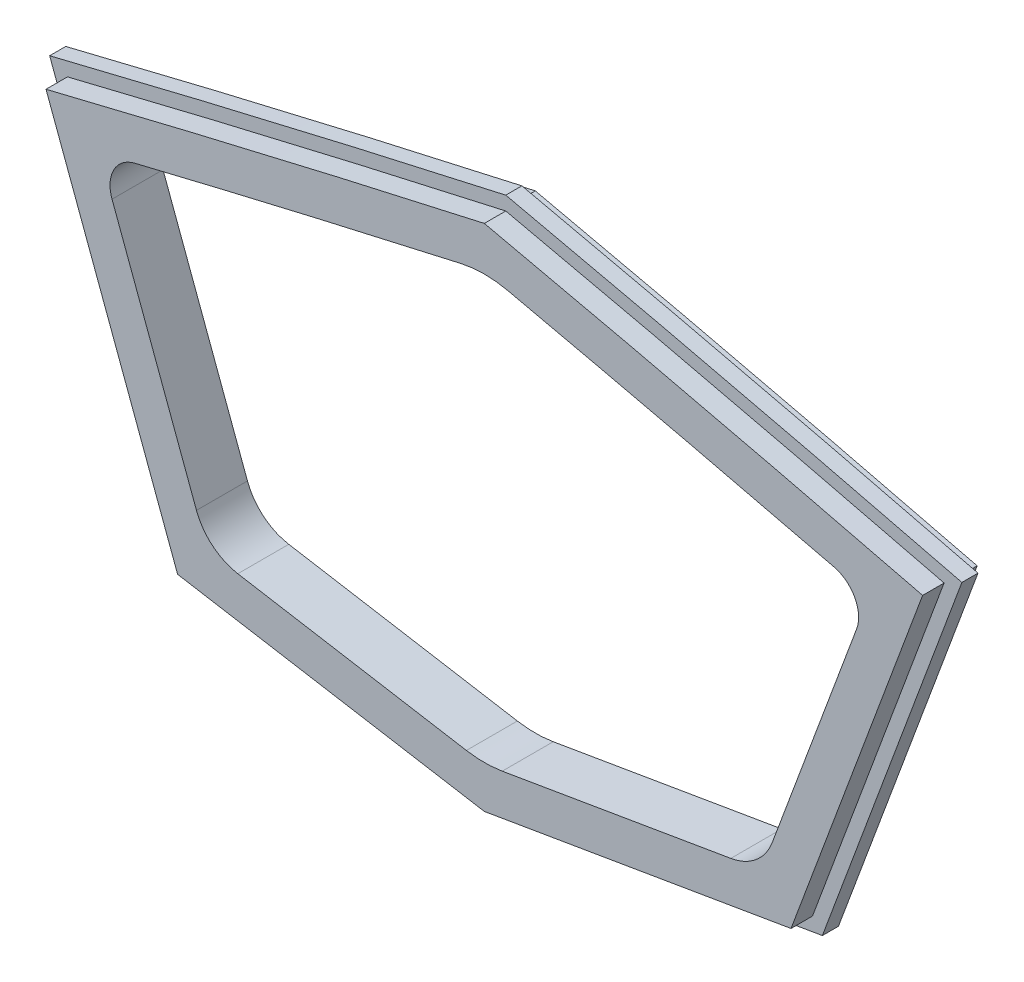
SolidWorks part; units mm, degrees
ref_plane "Front Plane" through (0, 0, 0) normal (0, 0, 1) x (1, 0, 0)
ref_plane "Top Plane" through (0, 0, 0) normal (0, 1, 0) x (1, 0, 0)
ref_plane "Right Plane" through (0, 0, 0) normal (1, 0, 0) x (0, 0, -1)
sketch "Sketch1" plane through (0, 0, 0) normal (0, 0, 1) x (1, 0, 0)
  line L0 (51.6321, -61.1055) -> (71.7233, -7.0229)
  line L1 (-71.7233, -7.0229) -> (-51.6321, -61.1055)
  line L2 (-51.6321, -61.1055) -> (0, -69.8574)
  line L3 (0, -69.8574) -> (51.6321, -61.1055)
  line L8 (58.9956, -70) -> (85, 0.0001)
  line L9 (0, -80) -> (58.9956, -70)
  line L10 (-58.9956, -70) -> (0, -80)
  line L11 (-85, 0.0001) -> (-58.9956, -70)
  spline S0 degree 1 poles (71.7233, -7.0229) (0, 9.7572) knots 0 0 1 1 construction
  spline S1 degree 1 poles (0, 9.7572) (-71.7233, -7.0229) knots 0 0 1 1 construction
  spline S4 degree 3 poles (0, 19.9999) (-28.4207, 13.7115) (-56.7505, 7.0175) (-85, 0.0001) knots 0 0 0 0 1 1 1 1
  spline S5 degree 3 poles (85, 0.0001) (56.7505, 7.0175) (28.4208, 13.7115) (0, 19.9999) knots 0 0 0 0 1 1 1 1
  spline S6 degree 3 poles (71.7233, -7.0229) (65.7602, -5.5606) (53.8262, -2.6655) (35.9064, 1.5822) (17.9654, 5.7307) (5.9913, 8.427) (0, 9.7572) knots 0.128509 0.128509 0.128509 0.128509 0.340026 0.551543 0.76306 0.974577 0.974577 0.974577 0.974577
  spline S7 degree 3 poles (0, 9.7572) (-5.9913, 8.427) (-17.9654, 5.7308) (-35.9064, 1.5822) (-53.8262, -2.6654) (-65.7603, -5.5605) (-71.7233, -7.0229) knots 0.025423 0.025423 0.025423 0.025423 0.23694 0.448457 0.659974 0.871491 0.871491 0.871491 0.871491
  dimension "D2" = 10
extrude "Boss-Extrude1" add sketch "Sketch1" along normal blind 3
fillet "Fillet1" radius 20 2 edges at (0, -69.8574, 1.5) (0, 9.7572, 1.5)
fillet "Fillet2" radius 10 2 edges at (51.6321, -61.1055, 1.5) (-51.6321, -61.1055, 1.5)
fillet "Fillet3" radius 6 2 edges at (71.7233, -7.0229, 1.5) (-71.7233, -7.0229, 1.5)
sketch "Sketch2" plane through (0, 0, 3) normal (0, 0, 1) x (1, 0, 0)
  line L4 (-69.376, -13.3415) -> (-53.6427, -55.6934) construction
  line L5 (-45.9398, -62.0704) -> (-3.3424, -69.2908) construction
  line L6 (3.3424, -69.2908) -> (45.9398, -62.0704) construction
  line L7 (53.6427, -55.6934) -> (69.376, -13.3416) construction
  line L8 (-81.682, -1.7527) -> (-57.1548, -67.7764)
  line L9 (-57.1548, -67.7764) -> (0, -77.4643)
  line L10 (0, -77.4643) -> (57.1548, -67.7764)
  line L11 (57.1548, -67.7764) -> (81.6819, -1.7527)
  line L12 (-81.682, -1.7527) -> (-57.1548, -67.7764)
  line L13 (-57.1548, -67.7764) -> (0, -77.4643)
  line L14 (0, -77.4643) -> (57.1548, -67.7764)
  line L15 (57.1548, -67.7764) -> (81.6819, -1.7527)
  line L16 (-69.376, -13.3415) -> (-53.6427, -55.6934)
  line L17 (-45.9398, -62.0704) -> (-3.3424, -69.2908)
  line L18 (3.3424, -69.2908) -> (45.9398, -62.0704)
  line L19 (53.6427, -55.6934) -> (69.376, -13.3416)
  arc A1 (-65.1699, -5.4221) -> (-69.376, -13.3415) centre (-63.7516, -11.2521) ccw construction
  arc A2 (-53.6427, -55.6934) -> (-45.9398, -62.0704) centre (-44.2686, -52.211) ccw construction
  arc A3 (-3.3424, -69.2908) -> (3.3424, -69.2908) centre (0, -49.5721) ccw construction
  arc A4 (45.9398, -62.0704) -> (53.6427, -55.6934) centre (44.2686, -52.211) ccw construction
  arc A5 (69.376, -13.3416) -> (65.1699, -5.4222) centre (63.7515, -11.2521) ccw construction
  arc A6 (4.3632, 8.7852) -> (-4.3632, 8.7852) centre (0, -10.7331) ccw construction
  arc A7 (-65.1699, -5.4221) -> (-69.376, -13.3415) centre (-63.7516, -11.2521) ccw
  arc A8 (-53.6427, -55.6934) -> (-45.9398, -62.0704) centre (-44.2686, -52.211) ccw
  arc A9 (-3.3424, -69.2908) -> (3.3424, -69.2908) centre (0, -49.5721) ccw
  arc A10 (45.9398, -62.0704) -> (53.6427, -55.6934) centre (44.2686, -52.211) ccw
  arc A11 (69.376, -13.3416) -> (65.1699, -5.4222) centre (63.7515, -11.2521) ccw
  arc A12 (4.3632, 8.7852) -> (-4.3632, 8.7852) centre (0, -10.7331) ccw
  spline S3 degree 3 poles (1947.6207, -293.2287) (956.0423, 113.109) (452.1928, 114.4463) (-35.9064, 1.5822) (-950.4936, -215.2091) (-1786.9263, -796.7733) (436.8515, 1741.9638) knots -16.603487 -16.603487 -16.603487 -16.603487 0.23694 0.448457 0.659974 32.623003 32.623003 32.623003 32.623003 only from (-4.3632, 8.7852) to (-65.1699, -5.4221) construction
  spline S4 degree 3 poles (2707.3086, 717.6059) (863.2892, -1925.7979) (-218.5935, 2016.9541) (-2398.1352, -1436.0722) knots -31.267069 -31.267069 -31.267069 -31.267069 26.357833 26.357833 26.357833 26.357833 only from (81.6819, -1.7527) to (0, 17.4394)
  spline S5 degree 3 poles (2395.6095, -1438.8298) (222.4353, 2021.2441) (-869.6893, -1931.6699) (-2703.2731, 723.3269) knots -25.368362 -25.368362 -25.368362 -25.368362 32.296868 32.296868 32.296868 32.296868 only from (0, 17.4394) to (-81.682, -1.7527)
  spline S6 degree 3 poles (81.6819, -1.7527) (54.5322, 4.9703) (27.3082, 11.392) (0, 17.4394) knots 0 0 0 0 1 1 1 1
  spline S7 degree 3 poles (0, 17.4394) (-27.3081, 11.392) (-54.5323, 4.9703) (-81.682, -1.7527) knots 0 0 0 0 1 1 1 1
  spline S8 degree 3 poles (-448.3337, 1741.5955) (1786.0704, -796.1529) (949.9918, -215.0912) (35.9064, 1.5822) (-452.7161, 114.5678) (-957.1703, 113.1138) (-1947.0313, -295.4162) knots -31.605284 -31.605284 -31.605284 -31.605284 0.340026 0.551543 0.76306 17.622017 17.622017 17.622017 17.622017 only from (65.1699, -5.4222) to (4.3632, 8.7852) construction
  spline S9 degree 3 poles (-4.3632, 8.7852) (-8.8983, 7.7714) (-19.4173, 5.395) (-35.9064, 1.5822) (-51.6385, -2.1469) (-61.389, -4.5023) (-65.1699, -5.4221) knots 0.076777 0.076777 0.076777 0.076777 0.23694 0.448457 0.659974 0.794023 0.794023 0.794023 0.794023
  spline S10 degree 3 poles (65.1699, -5.4222) (61.389, -4.5024) (51.6385, -2.1469) (35.9064, 1.5822) (19.4173, 5.395) (8.8983, 7.7714) (4.3632, 8.7852) knots 0.205976 0.205976 0.205976 0.205976 0.340026 0.551543 0.76306 0.923223 0.923223 0.923223 0.923223
  dimension "D1" = 2.5
extrude "Boss-Extrude2" add sketch "Sketch2" along normal blind 4
sketch "Sketch3" plane through (0, 0, 0) normal (0, 0, -1) x (-1, 0, 0)
  line L0 (69.376, -13.3415) -> (53.6427, -55.6934) construction
  line L1 (45.9398, -62.0704) -> (3.3424, -69.2908) construction
  line L2 (-3.3424, -69.2908) -> (-45.9398, -62.0704) construction
  line L3 (-53.6427, -55.6934) -> (-69.376, -13.3416) construction
  line L12 (57.5229, -68.2211) -> (82.3456, -1.4019)
  line L13 (0, -77.9715) -> (57.5229, -68.2211)
  line L14 (-57.5229, -68.2211) -> (0, -77.9715)
  line L15 (-82.3456, -1.402) -> (-57.5229, -68.2211)
  line L16 (57.5229, -68.2211) -> (82.3456, -1.4019)
  line L17 (0, -77.9715) -> (57.5229, -68.2211)
  line L18 (-57.5229, -68.2211) -> (0, -77.9715)
  line L19 (-82.3456, -1.402) -> (-57.5229, -68.2211)
  line L20 (-53.6427, -55.6934) -> (-69.376, -13.3416)
  line L21 (-3.3424, -69.2908) -> (-45.9398, -62.0704)
  line L22 (45.9398, -62.0704) -> (3.3424, -69.2908)
  line L23 (69.376, -13.3415) -> (53.6427, -55.6934)
  arc A0 (4.3632, 8.7852) -> (-4.3632, 8.7852) centre (0, -10.7331) ccw construction
  arc A1 (69.376, -13.3415) -> (65.1699, -5.4221) centre (63.7516, -11.2521) ccw construction
  arc A2 (45.9398, -62.0704) -> (53.6427, -55.6934) centre (44.2686, -52.211) ccw construction
  arc A3 (-3.3424, -69.2908) -> (3.3424, -69.2908) centre (0, -49.5721) ccw construction
  arc A4 (-53.6427, -55.6934) -> (-45.9398, -62.0704) centre (-44.2686, -52.211) ccw construction
  arc A5 (-65.1699, -5.4222) -> (-69.376, -13.3416) centre (-63.7515, -11.2521) ccw construction
  arc A6 (-65.1699, -5.4222) -> (-69.376, -13.3416) centre (-63.7515, -11.2521) ccw
  arc A7 (-53.6427, -55.6934) -> (-45.9398, -62.0704) centre (-44.2686, -52.211) ccw
  arc A8 (-3.3424, -69.2908) -> (3.3424, -69.2908) centre (0, -49.5721) ccw
  arc A9 (45.9398, -62.0704) -> (53.6427, -55.6934) centre (44.2686, -52.211) ccw
  arc A10 (69.376, -13.3415) -> (65.1699, -5.4221) centre (63.7516, -11.2521) ccw
  arc A11 (4.3632, 8.7852) -> (-4.3632, 8.7852) centre (0, -10.7331) ccw
  spline S0 degree 3 poles (-2856.2231, -710.7914) (-1223.1942, 104.564) (-579.2853, 143.8341) (35.9064, 1.5822) (1030.2564, -234.1159) (1933.2229, -901.7007) (-1099.9889, 2490.3845) knots -21.098589 -21.098589 -21.098589 -21.098589 0.23694 0.448457 0.659974 35.447452 35.447452 35.447452 35.447452 only from (4.3632, 8.7852) to (65.1699, -5.4221) construction
  spline S1 degree 3 poles (1113.3341, 2488.3803) (-1932.0695, -900.8143) (-1029.5812, -233.957) (-35.9064, 1.5822) (580.0364, 144.0085) (1224.8367, 104.4791) (2854.4298, -715.5725) knots -34.423595 -34.423595 -34.423595 -34.423595 0.340026 0.551543 0.76306 22.125182 22.125182 22.125182 22.125182 only from (-65.1699, -5.4222) to (-4.3632, 8.7852) construction
  spline S2 degree 3 poles (-65.1699, -5.4222) (-61.389, -4.5024) (-51.6385, -2.1469) (-35.9064, 1.5822) (-19.4173, 5.395) (-8.8983, 7.7714) (-4.3632, 8.7852) knots 0.205976 0.205976 0.205976 0.205976 0.340026 0.551543 0.76306 0.923223 0.923223 0.923223 0.923223
  spline S3 degree 3 poles (4.3632, 8.7852) (8.8983, 7.7714) (19.4173, 5.395) (35.9064, 1.5822) (51.6385, -2.1469) (61.389, -4.5023) (65.1699, -5.4221) knots 0.076777 0.076777 0.076777 0.076777 0.23694 0.448457 0.659974 0.794023 0.794023 0.794023 0.794023
  spline S6 degree 3 poles (2861.5507, -2335.4276) (177.3387, 3058.5283) (-915.4559, -2999.1622) (-3172.8289, 1634.1718) knots -31.712306 -31.712306 -31.712306 -31.712306 39.953767 39.953767 39.953767 39.953767 only from (0.0002, 17.9394) to (-82.3456, -1.402)
  spline S7 degree 3 poles (3162.1893, 1644.6134) (927.4674, -3008.9044) (-185.5325, 3065.7428) (-2855.6942, -2340.2467) knots -38.989826 -38.989826 -38.989826 -38.989826 32.725692 32.725692 32.725692 32.725692 only from (82.3456, -1.4019) to (0.0002, 17.9394)
  spline S8 degree 3 poles (0.0002, 17.9394) (-27.5313, 11.8519) (-54.9768, 5.379) (-82.3456, -1.402) knots -0.075105 -0.075105 -0.075105 -0.075105 1.011252 1.011252 1.011252 1.011252
  spline S9 degree 3 poles (82.3456, -1.4019) (54.977, 5.379) (27.5316, 11.8519) (0.0002, 17.9394) knots -0.011247 -0.011247 -0.011247 -0.011247 1.075105 1.075105 1.075105 1.075105
  dimension "D2" = 0
extrude "Boss-Extrude3" add sketch "Sketch3" along normal blind 2.5
